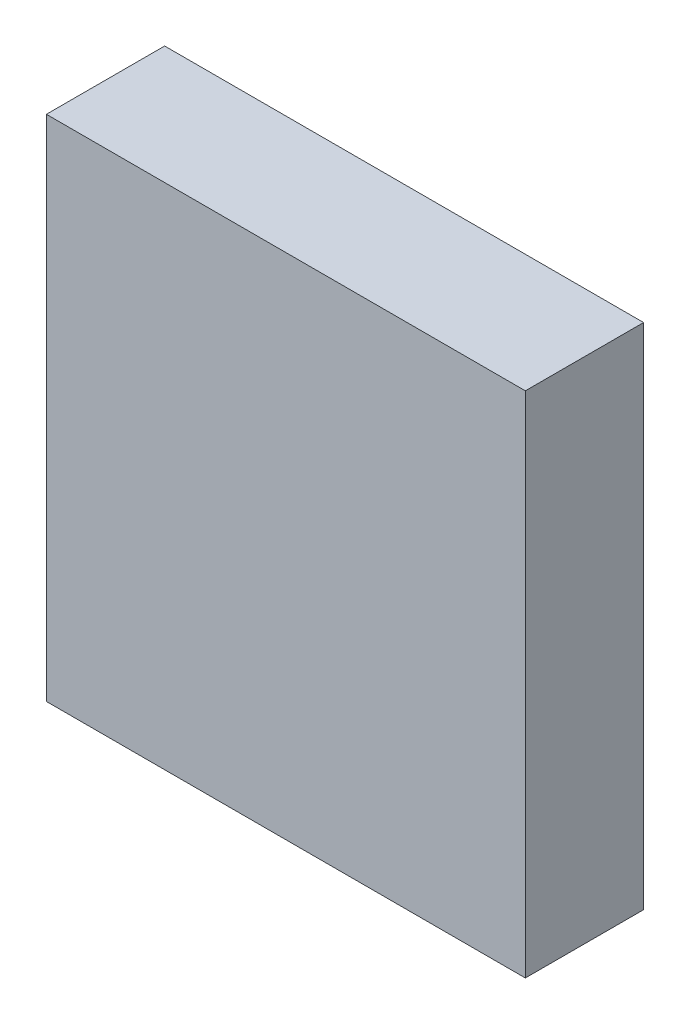
SolidWorks part; units mm, degrees
ref_plane "Front Plane" through (0, 0, 0) normal (0, 0, 1) x (1, 0, 0)
ref_plane "Top Plane" through (0, 0, 0) normal (0, 1, 0) x (1, 0, 0)
ref_plane "Right Plane" through (0, 0, 0) normal (1, 0, 0) x (0, 0, -1)
sketch "Sketch1" plane through (0, 0, 0) normal (0, 0, 1) x (1, 0, 0)
  line L1 (-40.5, -43) -> (40.5, -43)
  line L2 (-40.5, -43) -> (-40.5, 43)
  line L3 (-40.5, 43) -> (40.5, 43)
  line L4 (40.5, -43) -> (40.5, 43)
  line L5 (-40.5, -43) -> (40.5, 43) construction
  line L6 (-40.5, 43) -> (40.5, -43) construction
  point P0 (0, 0)
  dimension "D1" = 86
  dimension "D2" = 81
extrude "Boss-Extrude1" add sketch "Sketch1" along normal blind 20
